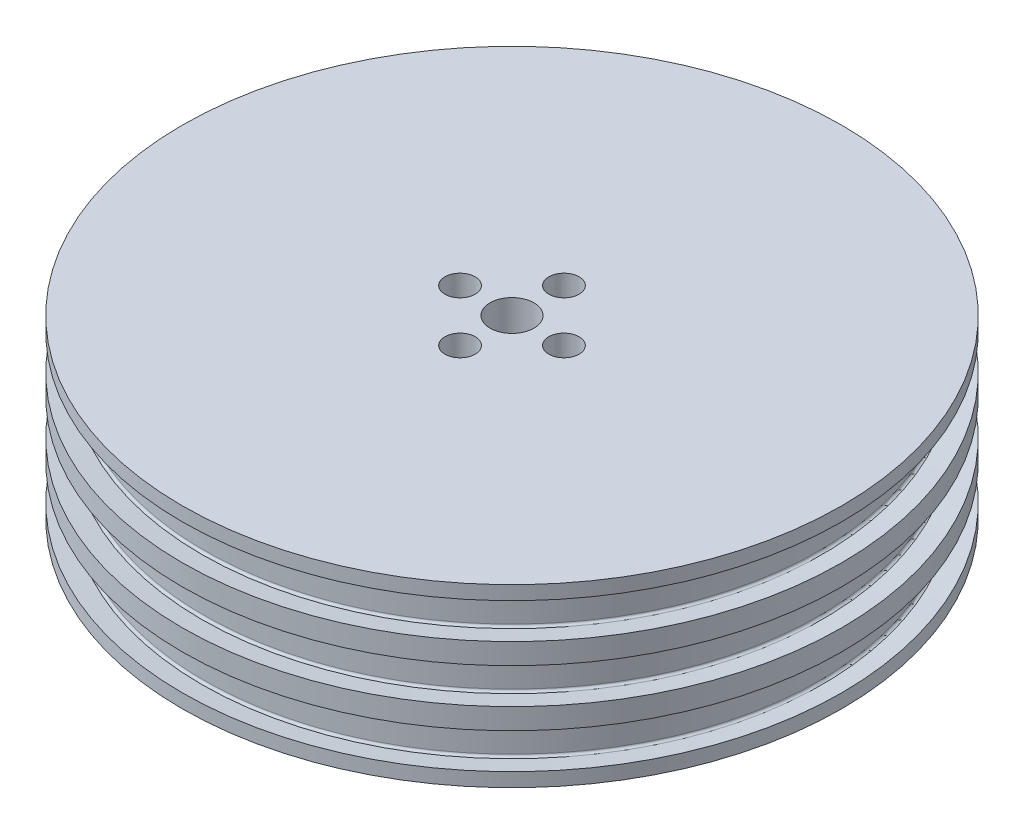
SolidWorks part; units mm, degrees
ref_plane "Front Plane" through (0, 0, 0) normal (0, 0, 1) x (1, 0, 0)
ref_plane "Top Plane" through (0, 0, 0) normal (0, 1, 0) x (1, 0, 0)
ref_plane "Right Plane" through (0, 0, 0) normal (1, 0, 0) x (0, 0, -1)
sketch "Sketch1" plane through (0, 0, 0) normal (0, 1, 0) x (1, 0, 0)
  circle A0 centre (0, 0) radius 38.1
  dimension "D1" = 76.2
extrude "Boss-Extrude1" add sketch "Sketch1" along normal blind 20.32
sketch "Sketch2" plane through (0, 0, 0) normal (1, 0, 0) x (0, 0, -1)
  line L0 (0, 0) -> (0, 20.32) construction
  line L1 (-38.1, 0) -> (38.1, 0) construction
  line L2 (38.1, 20.32) -> (-38.1, 20.32) construction
  line L3 (0, 16.6687) -> (-38.1, 16.6687) construction
  line L5 (-38.1, 20.32) -> (-38.1, 0) construction
  line L6 (0, 10.16) -> (-38.1, 10.16) construction
  line L8 (-40.64, 19.05) -> (-35.56, 19.05) construction
  line L9 (-40.64, 18.3812) -> (-40.64, 14.9563)
  line L10 (-40.64, 14.2875) -> (-35.56, 14.2875) construction
  line L11 (-35.56, 19.05) -> (-35.56, 14.2875)
  line L12 (-40.64, 19.05) -> (-35.56, 14.2875) construction
  line L13 (-40.64, 14.2875) -> (-35.56, 19.05) construction
  line L21 (-38.1, 20.32) -> (-38.1, 0) construction
  line L22 (-40.64, 11.8725) -> (-40.64, 8.4475)
  line L26 (-35.56, 19.05) -> (-40.64, 18.3812)
  line L27 (-35.56, 14.2875) -> (-40.64, 14.9563)
  line L28 (-35.56, 12.5413) -> (-35.56, 7.7787)
  line L29 (-35.56, 12.5413) -> (-40.64, 11.8725)
  line L30 (-35.56, 7.7787) -> (-40.64, 8.4475)
  line L31 (-40.64, 5.3637) -> (-40.64, 1.9388)
  line L32 (-35.56, 6.0325) -> (-35.56, 1.27)
  line L33 (-35.56, 6.0325) -> (-40.64, 5.3637)
  line L34 (-35.56, 1.27) -> (-40.64, 1.9388)
  line L35 (-38.1, 10.16) -> (-40.64, 10.16) construction
  dimension "D1" = 5.08
  dimension "D2" = 1.27
  dimension "D3" = 4.7625
  dimension "D4" = 7.5
  dimension "D6" = 3
revolve "Cut-Revolve1" cut sketch "Sketch2" angle 360 about L0
fillet "Fillet1" radius 0.254 6 edges at (0, 19.05, -35.56) (0, 14.2875, -35.56) (0, 12.5413, -35.56) (0, 7.7787, -35.56) (0, 1.27, -35.56) (0, 6.0325, -35.56)
sketch "Sketch3" plane through (0, 0, 0) normal (0, -1, 0) x (1, 0, 0)
  circle A0 centre (0, 0) radius 2.54
  dimension "D1" = 5.08
extrude "Cut-Extrude1" cut sketch "Sketch3" against normal through all
sketch "Sketch4" plane through (0, 0, 0) normal (0, -1, 0) x (1, 0, 0)
  circle A0 centre (0, 0) radius 12.7
  dimension "D1" = 25.4
extrude "Cut-Extrude2" cut sketch "Sketch4" against normal blind 10.16
sketch "Sketch5" plane through (0, 10.16, 0) normal (0, -1, 0) x (1, 0, 0)
  circle A0 centre (0, 0) radius 6 construction
  circle A1 centre (0, 6) radius 1.75
  circle A2 centre (6, 0) radius 1.75
  circle A3 centre (0, -6) radius 1.75
  circle A4 centre (-6, 0) radius 1.75
  dimension "D1" = 3.5
  dimension "D2" = 12
extrude "Cut-Extrude3" cut sketch "Sketch5" against normal blind 12.7
sketch "Sketch6" plane through (0, 10.16, 0) normal (0, -1, 0) x (1, 0, 0)
  circle A0 centre (-6, 0) radius 1.75 construction
  circle A1 centre (0, -6) radius 1.75 construction
  circle A2 centre (6, 0) radius 1.75 construction
  circle A3 centre (0, 6) radius 1.75 construction
  circle A4 centre (-6, 0) radius 1.75
  circle A5 centre (0, -6) radius 1.75
  circle A6 centre (6, 0) radius 1.75
  circle A7 centre (0, 6) radius 1.75
  arc A8 (-3.4495, 3.4495) -> (-3.4495, -3.4495) centre (-6, 0) ccw
  arc A9 (-3.4495, -3.4495) -> (3.4495, -3.4495) centre (0, -6) ccw
  arc A10 (3.4495, -3.4495) -> (3.4495, 3.4495) centre (6, 0) ccw
  circle A12 centre (-6, 0) radius 4.29 construction
  circle A14 centre (0, -6) radius 4.29 construction
  circle A15 centre (6, 0) radius 4.29 construction
  arc A16 (3.4495, 3.4495) -> (-3.4495, 3.4495) centre (0, 6) ccw
  dimension "D1" = 2.54
extrude "Cut-Extrude4" cut sketch "Sketch6" against normal blind 5.08
